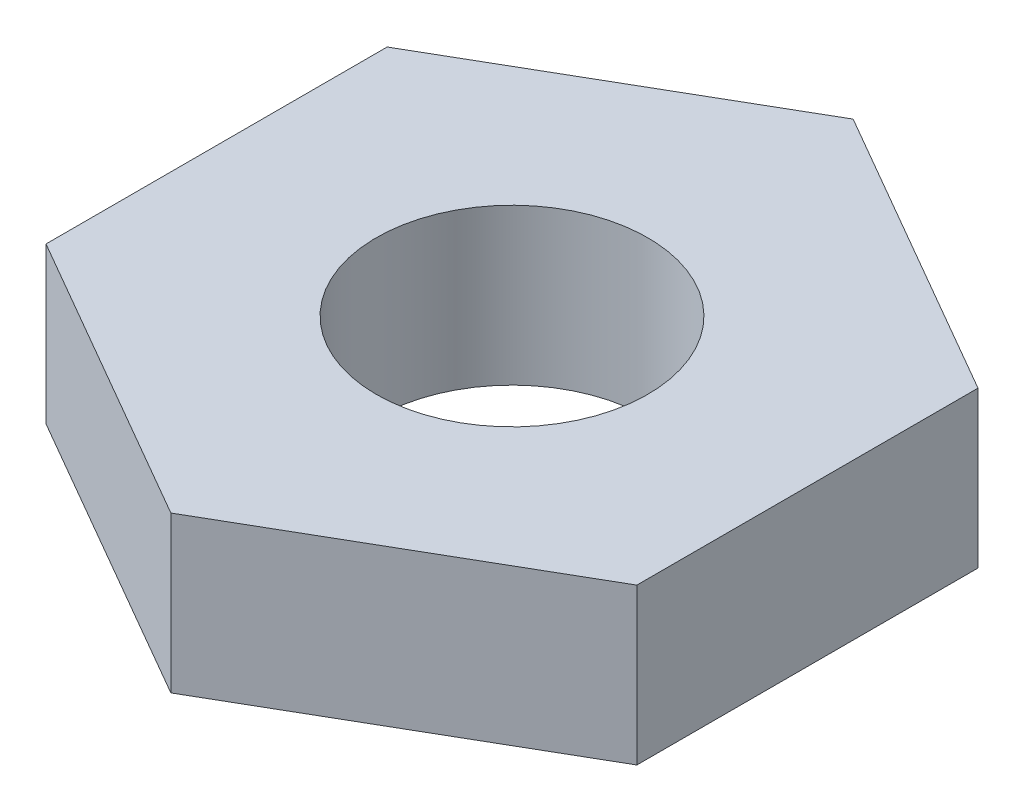
SolidWorks part; units mm, degrees
material "Cast Stainless Steel"
ref_plane "Front Plane" through (0, 0, 0) normal (0, 0, 1) x (1, 0, 0)
ref_plane "Top Plane" through (0, 0, 0) normal (0, 1, 0) x (1, 0, 0)
ref_plane "Right Plane" through (0, 0, 0) normal (1, 0, 0) x (0, 0, -1)
sketch "Sketch1" plane through (0, 0, 0) normal (0, 1, 0) x (1, 0, 0)
  line L6 (-3.1786, 1.8352) -> (0, 3.6703)
  line L7 (0, 3.6703) -> (3.1786, 1.8351)
  line L8 (3.1786, 1.8351) -> (3.1786, -1.8352)
  line L9 (3.1786, -1.8352) -> (0, -3.6703)
  line L10 (0, -3.6703) -> (-3.1786, -1.8351)
  line L11 (-3.1786, -1.8351) -> (-3.1786, 1.8352)
  circle A0 centre (0, 0) radius 1.4605
  point P12 (0, 0)
extrude "Boss-Extrude1" add sketch "Sketch1" along normal blind 1.6764
